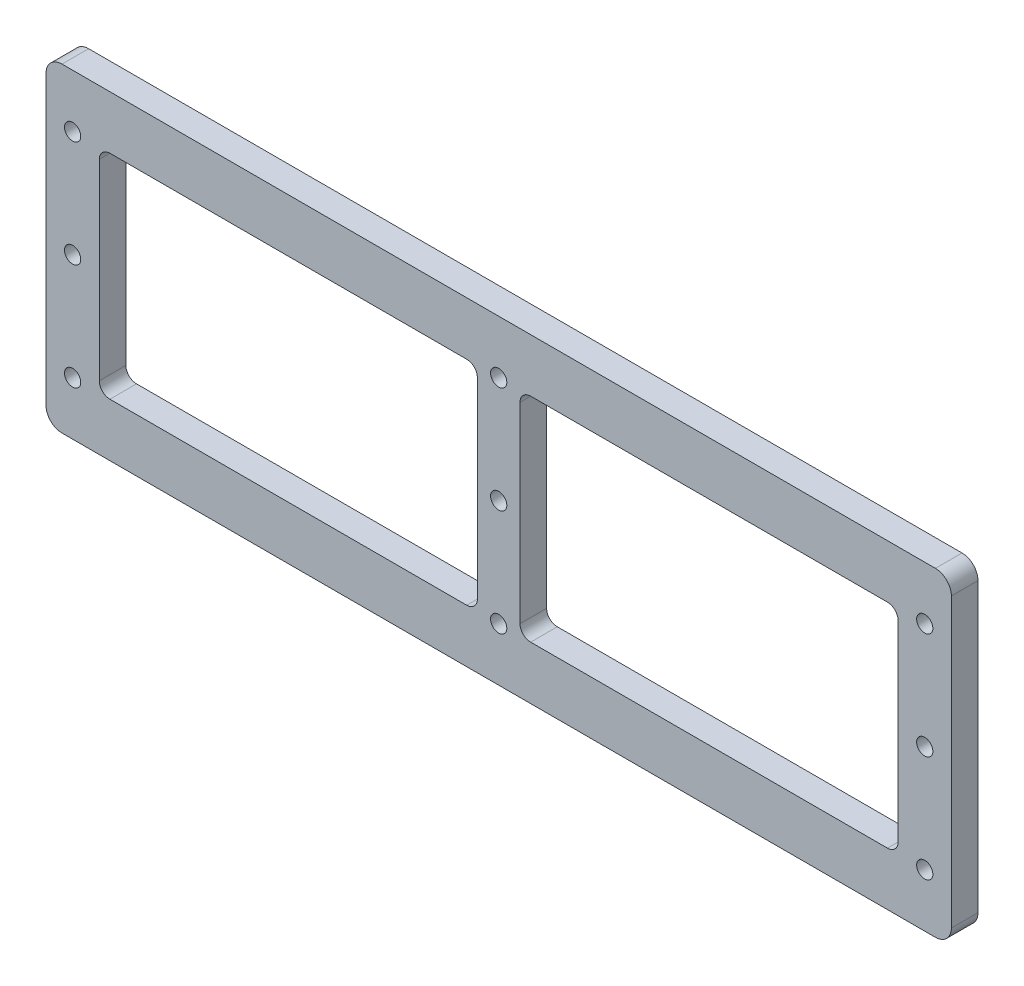
SolidWorks part; units mm, degrees
material "Thornel Mat VMA"
ref_plane "前视基准面" through (0, 0, 0) normal (0, 0, 1) x (1, 0, 0)
ref_plane "上视基准面" through (0, 0, 0) normal (0, 1, 0) x (1, 0, 0)
ref_plane "右视基准面" through (0, 0, 0) normal (1, 0, 0) x (0, 0, -1)
sketch "草图1" plane through (0, 0, 0) normal (0, 0, 1) x (1, 0, 0)
  line L1 (-85, -30) -> (85, -30)
  line L2 (-85, -30) -> (-85, 30)
  line L3 (-85, 30) -> (85, 30)
  line L4 (85, -30) -> (85, 30)
  line L5 (0, 30) -> (0, -30) construction
  line L6 (-85, 0) -> (85, 0) construction
  point P0 (0, 0)
  dimension "D1" = 60
  dimension "D2" = 170
extrude "凸台-拉伸1" add sketch "草图1" along normal blind 5
sketch "草图2" plane through (0, 0, 5) normal (0, 0, 1) x (1, 0, 0)
  line L0 (85, 30) -> (-85, 30) construction
  line L1 (-75, -20) -> (75, -20)
  line L2 (-75, -20) -> (-75, 20)
  line L3 (-75, 20) -> (75, 20)
  line L4 (75, -20) -> (75, 20)
  line L5 (0, 20) -> (0, -20) construction
  line L6 (-75, 0) -> (75, 0) construction
  line L7 (85, -30) -> (85, 30) construction
  line L8 (-85, 30) -> (-85, -30) construction
  line L9 (-85, -30) -> (85, -30) construction
  point P0 (0, 0)
  dimension "D1" = 10
  dimension "D2" = 10
  dimension "D3" = 10
  dimension "D4" = 10
extrude "切除-拉伸1" cut sketch "草图2" against normal blind 5
sketch "草图3" plane through (0, 0, 5) normal (0, 0, 1) x (1, 0, 0)
  line L0 (75, 20) -> (-75, 20) construction
  line L1 (-4, -20) -> (4, -20)
  line L2 (-4, -20) -> (-4, 20)
  line L3 (-4, 20) -> (4, 20)
  line L4 (4, -20) -> (4, 20)
  line L5 (0, 20) -> (0, -20) construction
  line L6 (-4, 0) -> (4, 0) construction
  point P0 (0, 0)
  dimension "D1" = 8
extrude "凸台-拉伸2" add sketch "草图3" against normal up to surface (5 mm away) up to face at (0, 0, 0)
fillet "圆角1" radius 3 4 edges at (-85, 30, 2.5) (-85, -30, 2.5) (85, -30, 2.5) (85, 30, 2.5)
fillet "圆角2" radius 2 8 edges at (-75, -20, 2.5) (-4, 20, 2.5) (-4, -20, 2.5) (4, 20, 2.5) (75, 20, 2.5) (75, -20, 2.5) (4, -20, 2.5) (-75, 20, 2.5)
sketch "草图4" plane through (0, 0, 0) normal (0, 0, -1) x (-1, 0, 0)
  line L0 (-80, 20) -> (80, 20) construction
  line L2 (0, 20) -> (0, 0) construction
  line L3 (6, 20) -> (73, 20) construction
  line L4 (-75, -18) -> (-75, 18) construction
  line L6 (-80, -20) -> (80, -20) construction
  line L7 (-80, -20) -> (-80, 20) construction
  line L8 (-80, 20) -> (80, 20) construction
  line L9 (80, -20) -> (80, 20) construction
  line L10 (0, 20) -> (0, -20) construction
  line L11 (-80, 0) -> (80, 0) construction
  circle A0 centre (80, 20) radius 1.525
  circle A1 centre (80, 0) radius 1.525
  circle A2 centre (0, -20) radius 1.525
  circle A3 centre (0, 20) radius 1.525
  circle A4 centre (-80, 20) radius 1.525
  circle A5 centre (-80, 0) radius 1.525
  circle A6 centre (-80, -20) radius 1.525
  circle A7 centre (0, 0) radius 1.525
  circle A8 centre (80, -20) radius 1.525
  point P3 (0, 20)
  dimension "D3" = 3.05
  dimension "D2" = 5
extrude "切除-拉伸2" cut sketch "草图4" against normal up to surface (5 mm away) up to face at (39.5, 0, 5)
equation "\"D2@草图2\"=\"D3@草图2\""
equation "\"D4@草图2\"=\"D1@草图2\""
